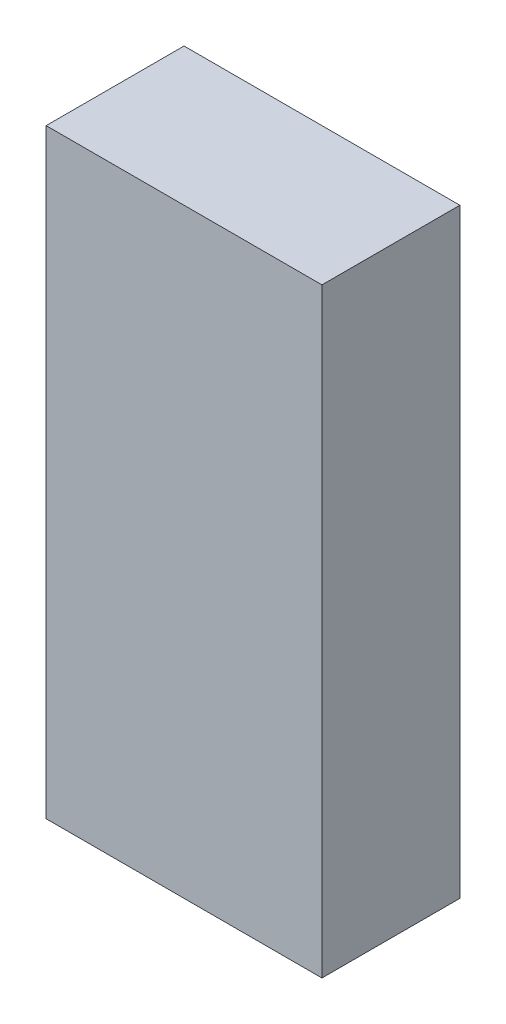
SolidWorks part; units mm, degrees
ref_plane "Front Plane" through (0, 0, 0) normal (0, 0, 1) x (1, 0, 0)
ref_plane "Top Plane" through (0, 0, 0) normal (0, 1, 0) x (1, 0, 0)
ref_plane "Right Plane" through (0, 0, 0) normal (1, 0, 0) x (0, 0, -1)
sketch "Sketch1" plane through (0, 0, 0) normal (0, 0, 1) x (1, 0, 0)
  line L0 (400, 625) -> (150, 625)
  line L1 (-425, 925) -> (425, 925)
  line L2 (-425, 925) -> (-425, -925)
  line L3 (-425, -925) -> (425, -925)
  line L4 (425, 925) -> (425, -925)
  line L5 (-425, 925) -> (425, -925) construction
  line L6 (-425, -925) -> (425, 925) construction
  line L7 (400, 900) -> (150, 900)
  line L8 (400, 900) -> (400, 650)
  line L9 (400, 650) -> (150, 650)
  line L10 (150, 900) -> (150, 650)
  line L11 (125, 650) -> (-125, 650)
  line L12 (125, 650) -> (125, 900)
  line L13 (125, 900) -> (-125, 900)
  line L14 (-125, 650) -> (-125, 900)
  line L15 (-150, 900) -> (-400, 900)
  line L16 (-150, 900) -> (-150, 650)
  line L17 (-150, 650) -> (-400, 650)
  line L18 (-400, 900) -> (-400, 650)
  line L19 (400, 625) -> (400, 375)
  line L20 (400, 375) -> (150, 375)
  line L21 (150, 625) -> (150, 375)
  line L22 (125, 375) -> (-125, 375)
  line L23 (125, 375) -> (125, 625)
  line L24 (125, 625) -> (-125, 625)
  line L25 (-125, 375) -> (-125, 625)
  line L26 (-150, 625) -> (-400, 625)
  line L27 (-150, 625) -> (-150, 375)
  line L28 (-150, 375) -> (-400, 375)
  line L29 (-400, 625) -> (-400, 375)
  line L30 (400, 350) -> (150, 350)
  line L31 (400, 350) -> (400, 100)
  line L32 (400, 100) -> (150, 100)
  line L33 (150, 350) -> (150, 100)
  line L34 (125, 100) -> (-125, 100)
  line L35 (125, 100) -> (125, 350)
  line L36 (125, 350) -> (-125, 350)
  line L37 (-125, 100) -> (-125, 350)
  line L38 (-150, 350) -> (-400, 350)
  line L39 (-150, 350) -> (-150, 100)
  line L40 (-150, 100) -> (-400, 100)
  line L41 (-400, 350) -> (-400, 100)
  point P0 (0, 0)
  dimension "D1" = 850
  dimension "D2" = 1850
  dimension "D3" = 25
  dimension "D4" = 25
  dimension "D5" = 250
  dimension "D6" = 250
  dimension "D7" = 250
  dimension "D8" = 250
  dimension "D9" = 25
  dimension "D10" = 25
  dimension "D11" = 3
extrude "Boss-Extrude1" add sketch "Sketch1" along normal blind 400
sketch "Sketch2" plane through (0, 0, 400) normal (0, 0, 1) x (1, 0, 0)
  line L1 (-425, 925) -> (425, 925)
  line L2 (-425, 925) -> (-425, -925)
  line L3 (-425, -925) -> (425, -925)
  line L4 (425, 925) -> (425, -925)
extrude "Boss-Extrude2" add sketch "Sketch2" along normal blind 25
